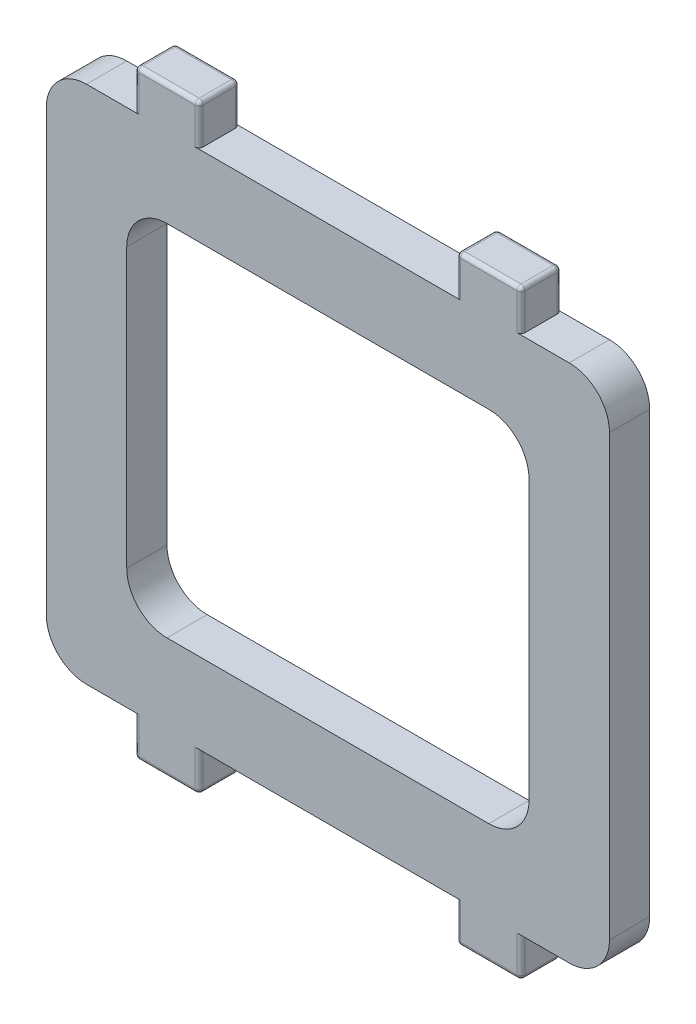
SolidWorks part; units mm, degrees
ref_plane "Alzado" through (0, 0, 0) normal (0, 0, 1) x (1, 0, 0)
ref_plane "Planta" through (0, 0, 0) normal (0, 1, 0) x (1, 0, 0)
ref_plane "Vista lateral" through (0, 0, 0) normal (1, 0, 0) x (0, 0, -1)
sketch "Croquis1" plane through (0, 0, 0) normal (0, 0, 1) x (1, 0, 0)
  line L1 (35, -32.3) -> (-35, -32.3)
  line L2 (35, -32.3) -> (35, 32.3)
  line L3 (35, 32.3) -> (-35, 32.3)
  line L4 (-35, -32.3) -> (-35, 32.3)
  line L5 (35, -32.3) -> (-35, 32.3) construction
  line L6 (35, 32.3) -> (-35, -32.3) construction
  line L7 (25, -22.3) -> (-25, -22.3)
  line L8 (25, -22.3) -> (25, 22.3)
  line L9 (25, 22.3) -> (-25, 22.3)
  line L10 (-25, -22.3) -> (-25, 22.3)
  line L11 (25, -22.3) -> (-25, 22.3) construction
  line L12 (25, 22.3) -> (-25, -22.3) construction
  point P0 (0, 0)
  point P6 (0, 0)
  dimension "D1" = 64.6
  dimension "D2" = 70
  dimension "D3" = 10
  dimension "D4" = 10
extrude "Saliente-Extruir1" add sketch "Croquis1" along normal blind 5
sketch "Croquis2" plane through (0, -32.3, 0) normal (0, -1, 0) x (1, 0, 0)
  line L0 (-35, 0) -> (35, 0) construction
  line L1 (-24, 0) -> (-16, 0)
  line L2 (-24, 0) -> (-24, 5)
  line L3 (-24, 5) -> (-16, 5)
  line L4 (-16, 0) -> (-16, 5)
  line L5 (-35, 5) -> (35, 5) construction
  line L6 (0, 0) -> (0, 9.041) construction
  line L7 (16, 0) -> (16, 5)
  line L8 (24, 5) -> (16, 5)
  line L9 (24, 0) -> (24, 5)
  line L10 (24, 0) -> (16, 0)
  point P8 (-20, 0)
  dimension "D1" = 8
  dimension "D2" = 20
extrude "Saliente-Extruir2" add sketch "Croquis2" along normal blind 5
fillet "Redondeo1" radius 0.5 16 edges at (16, -37.3, 2.5) (20, -37.3, 5) (24, -37.3, 2.5) (20, -37.3, 0) (-20, -37.3, 5) (-16, -37.3, 2.5) (-20, -37.3, 0) (-24, -37.3, 2.5) (16, -34.8, 0) (24, -34.8, 0) (24, -34.8, 5) (16, -34.8, 5) (-24, -34.8, 0) (-16, -34.8, 0) (-24, -34.8, 5) (-16, -34.8, 5)
mirror "Simetría1" about plane through (0, 0, 0) normal (0, 1, 0) of "Saliente-Extruir2", "Redondeo1"
fillet "Redondeo2" radius 5 8 edges at (35, -32.3, 2.5) (-35, -32.3, 2.5) (-35, 32.3, 2.5) (35, 32.3, 2.5) (-25, -22.3, 2.5) (25, -22.3, 2.5) (25, 22.3, 2.5) (-25, 22.3, 2.5)
